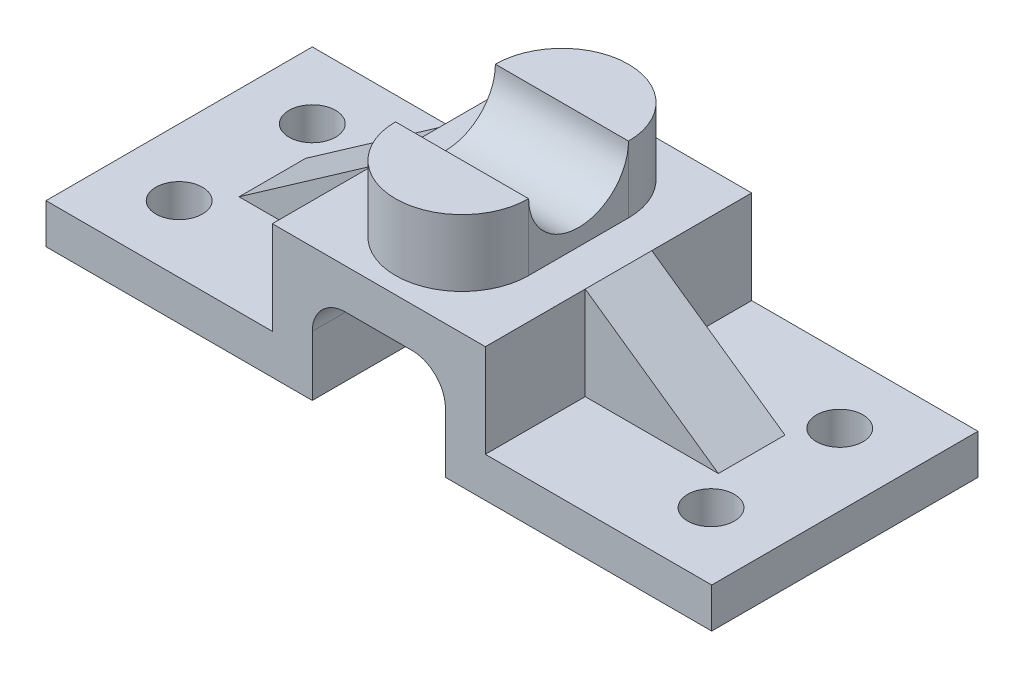
SolidWorks part; units mm, degrees
ref_plane "Ön Düzlem" through (0, 0, 0) normal (0, 0, 1) x (1, 0, 0)
ref_plane "Üst Düzlem" through (0, 0, 0) normal (0, 1, 0) x (1, 0, 0)
ref_plane "Sağ Düzlem" through (0, 0, 0) normal (1, 0, 0) x (0, 0, -1)
sketch "Sketch1" plane through (0, 0, 0) normal (0, 1, 0) x (1, 0, 0)
  line L1 (-76.3205, 15.3601) -> (23.6795, 15.3601)
  line L2 (-76.3205, 15.3601) -> (-76.3205, -24.6399)
  line L3 (-76.3205, -24.6399) -> (23.6795, -24.6399)
  line L4 (23.6795, 15.3601) -> (23.6795, -24.6399)
  circle A0 centre (-66.3205, 5.3601) radius 3.5
  circle A1 centre (-66.3205, -14.6399) radius 3.5
  circle A2 centre (12.9129, 5.3601) radius 3.5
  circle A3 centre (13.5739, -14.6399) radius 3.5
extrude "Boss-Extrude1" add sketch "Sketch1" along normal blind 6
sketch "Sketch2" plane through (0, 6, 0) normal (0, 1, 0) x (1, 0, 0)
  line L0 (-76.3205, -24.6399) -> (-42.3205, -24.6399)
  line L1 (-76.3205, -24.6399) -> (23.6795, -24.6399) construction
  line L2 (-42.3205, -24.6399) -> (-42.3205, 15.3601)
  line L3 (23.6795, 15.3601) -> (-76.3205, 15.3601) construction
  line L4 (-42.3205, -24.6399) -> (-10.3205, -24.6399)
  line L5 (-10.3205, -24.6399) -> (-10.3205, 15.3601)
  line L6 (-10.3205, 15.3601) -> (-42.3205, 15.3601)
  line M6 (-76.3205, -24.6399) -> (23.6795, -24.6399)
  line M8 (23.6795, 15.3601) -> (-76.3205, 15.3601)
extrude "Boss-Extrude2" add sketch "Sketch2" along normal blind 14 contours L5 L2 M6 M8
sketch "Sketch3" plane through (0, 0, 0) normal (0, -1, 0) x (1, 0, 0)
  line L1 (-76.3205, 24.6399) -> (23.6795, 24.6399) construction
  line L2 (-36.3205, 24.6399) -> (-36.3205, -15.3601)
  line L3 (23.6795, -15.3601) -> (-76.3205, -15.3601) construction
  line L4 (-36.3205, -15.3601) -> (-16.3205, -15.3601)
  line L5 (-16.3205, -15.3601) -> (-16.3205, 24.6399)
  line L6 (-16.3205, 24.6399) -> (-36.3205, 24.6399)
extrude "Cut-Extrude1" cut sketch "Sketch3" against normal blind 14
fillet "Fillet2" radius 5 1 edges at (-36.3205, 14, 4.6399)
fillet "Fillet3" radius 5 1 edges at (-16.3205, 14, 4.6399)
sketch "Sketch5" plane through (0, 6, 0) normal (0, 1, 0) x (1, 0, 0)
  line L0 (-10.3205, -24.6399) -> (-10.3205, -9.6399)
  line L1 (-10.3205, -24.6399) -> (-10.3205, 15.3601) construction
ref_plane "Plane1" through (0, 0, 9.6399) normal (0, 0, 1) x (1, 0, 0)
sketch "Sketch6" plane through (0, 0, 9.6399) normal (0, 0, 1) x (1, 0, 0)
  line L0 (-10.3205, 6) -> (9.6795, 6)
  line L1 (-10.3205, 6) -> (23.6795, 6) construction
  line L2 (9.6795, 6) -> (-10.3205, 20)
  line L3 (-10.3205, 20) -> (-10.3205, 6)
  line L4 (-42.3205, 6) -> (-62.3205, 6)
  line L5 (-76.3205, 6) -> (-42.3205, 6) construction
  line L6 (-62.3205, 6) -> (-42.3205, 20)
  line L7 (-42.3205, 20) -> (-42.3205, 6)
extrude "Boss-Extrude3" add sketch "Sketch6" against normal blind 10
sketch "Sketch7" plane through (0, 20, 0) normal (0, 1, 0) x (1, 0, 0)
  line L0 (-26.3205, 2.8601) -> (-26.3205, -12.1399) construction
  line L1 (-16.3205, 2.8601) -> (-16.3205, -12.1399)
  line L2 (-36.3205, 2.8601) -> (-36.3205, -12.1399)
  arc A0 (-16.3205, 2.8601) -> (-36.3205, 2.8601) centre (-26.3205, 2.8601) ccw
  arc A1 (-36.3205, -12.1399) -> (-16.3205, -12.1399) centre (-26.3205, -12.1399) ccw
  point P2 (-26.3205, -4.6399)
extrude "Boss-Extrude4" add sketch "Sketch7" along normal blind 10
sketch "Sketch8" plane through (-16.3205, 0, 0) normal (1, 0, 0) x (0, 0, -1)
  line L0 (-12.1399, 30) -> (2.8601, 30) construction
  circle A0 centre (-4.6399, 30) radius 7.5
extrude "Cut-Extrude2" cut sketch "Sketch8" against normal blind 29
